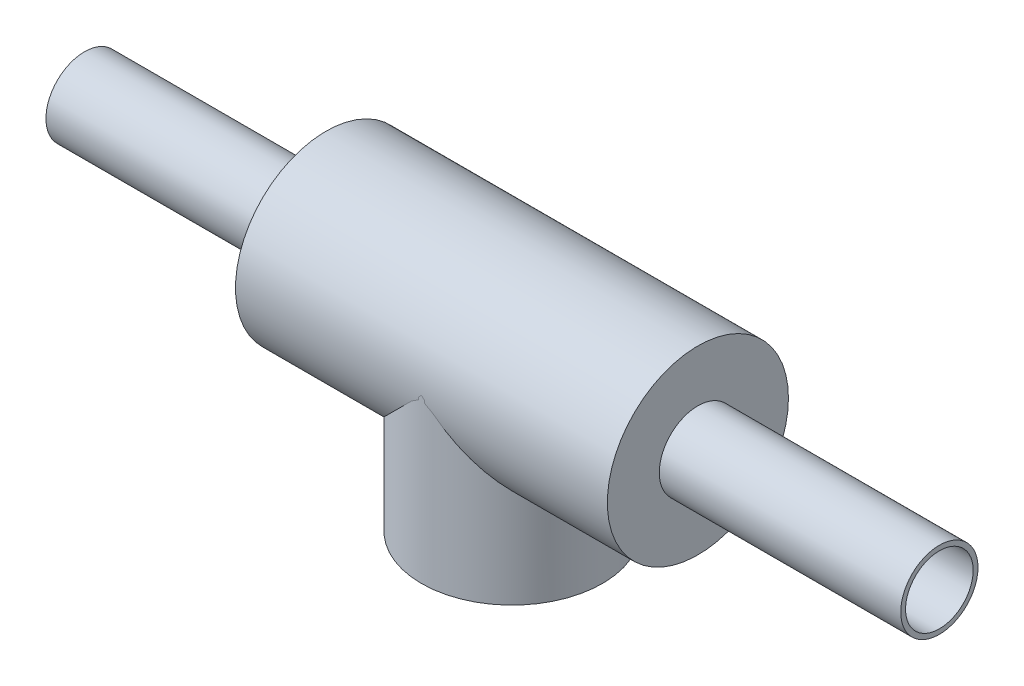
SolidWorks part; units mm, degrees
ref_plane "前视基准面" through (0, 0, 0) normal (0, 0, 1) x (1, 0, 0)
ref_plane "上视基准面" through (0, 0, 0) normal (0, 1, 0) x (1, 0, 0)
ref_plane "右视基准面" through (0, 0, 0) normal (1, 0, 0) x (0, 0, -1)
sketch "草图1" plane through (0, 0, 0) normal (0, 0, 1) x (1, 0, 0)
  circle A0 centre (0, 0) radius 37.5
  circle A1 centre (0, 0) radius 35
  dimension "D1" = 75
  dimension "D2" = 70
sketch "草图2" plane through (0, 0, 0) normal (1, 0, 0) x (0, 0, -1)
  line L0 (0, 0) -> (40, 0)
  line L1 (80, 40) -> (80, 120)
  arc A0 (80, 40) -> (40, 0) centre (40, 40) cw
  point P6 (80, 0)
  dimension "D3" = 40
  dimension "D1" = 80
  dimension "D2" = 120
sweep "扫描2" add profiles "草图1" path "草图2"
sketch "草图4" plane through (0, 0, 0) normal (1, 0, 0) x (0, 0, -1)
  line L0 (115, 120) -> (45, 120) construction
  circle A0 centre (80, 120) radius 37.5
  circle A1 centre (80, 120) radius 35
  dimension "D1" = 70
extrude "凸台-拉伸1" add sketch "草图4" along normal mid plane 150
sketch "草图5" plane through (75, 0, 0) normal (1, 0, 0) x (0, 0, -1)
  circle A0 centre (80, 120) radius 37.5
  circle A1 centre (80, 120) radius 37.5 construction
  circle A2 centre (80, 120) radius 14
  dimension "D1" = 28
extrude "凸台-拉伸2" add sketch "草图5" along normal blind 2
sketch "草图6" plane through (77, 0, 0) normal (1, 0, 0) x (0, 0, -1)
  circle A0 centre (80, 120) radius 16
  circle A1 centre (80, 120) radius 14
  dimension "D1" = 28
  dimension "D2" = 32
extrude "凸台-拉伸3" add sketch "草图6" along normal blind 100
mirror "镜向1" about plane through (0, 0, 0) normal (1, 0, 0) of "凸台-拉伸2", "凸台-拉伸3"
sketch "草图7" plane through (0, 0, 0) normal (0, 0, 1) x (1, 0, 0)
  line L0 (-77, 82.5) -> (-37.5, 82.5) construction
  line L1 (82.0436, -52.5) -> (-82.0436, -52.5)
  line L2 (82.0436, -52.5) -> (82.0436, 52.5)
  line L3 (82.0436, 52.5) -> (-82.0436, 52.5)
  line L4 (-82.0436, -52.5) -> (-82.0436, 52.5)
  line L5 (82.0436, -52.5) -> (-82.0436, 52.5) construction
  line L6 (82.0436, 52.5) -> (-82.0436, -52.5) construction
  point P0 (0, 0)
  dimension "D1" = 30
extrude "切除-拉伸1" cut sketch "草图7" against normal through all
sketch "草图8" plane through (0, 52.5, 0) normal (0, -1, 0) x (1, 0, 0)
  line L0 (-35, -80) -> (35, -80) construction
  circle A0 centre (0, -80) radius 35 construction
  circle A1 centre (0, -80) radius 35 construction
ref_plane "基准面1" through (0, 0, -80) normal (0, 0, -1) x (1, 0, 0)
